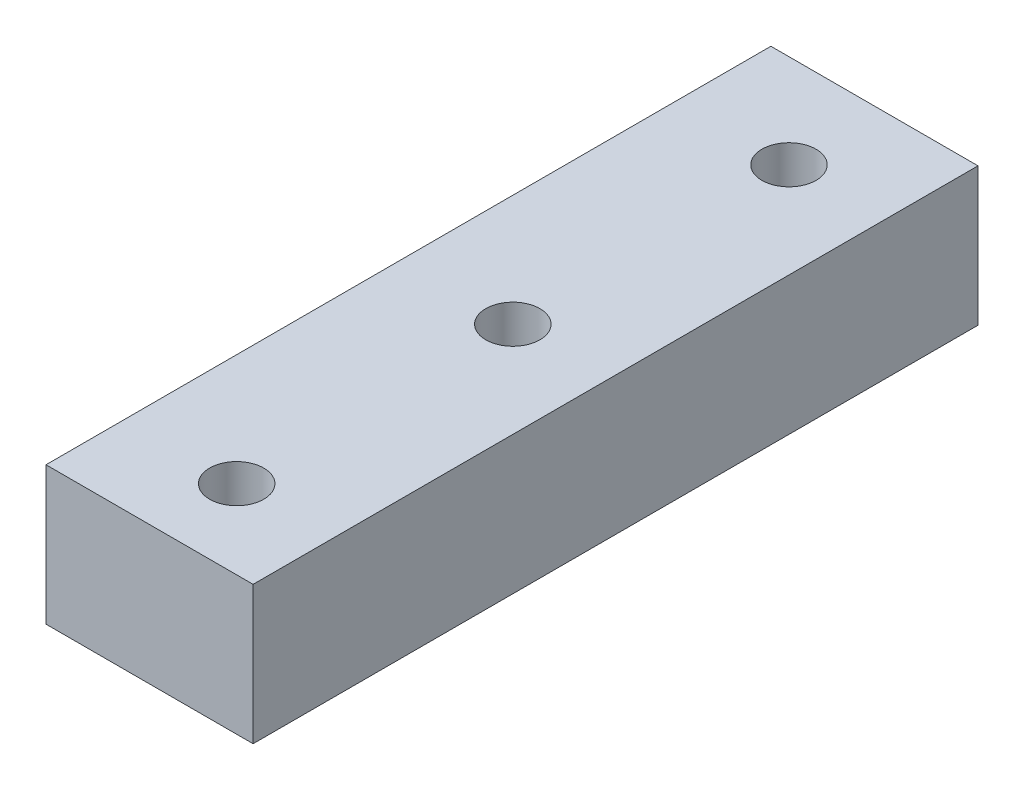
SolidWorks part; units mm, degrees
ref_plane "Front Plane" through (0, 0, 0) normal (0, 0, 1) x (1, 0, 0)
ref_plane "Top Plane" through (0, 0, 0) normal (0, 1, 0) x (1, 0, 0)
ref_plane "Right Plane" through (0, 0, 0) normal (1, 0, 0) x (0, 0, -1)
sketch "Sketch4" plane through (0, 0, 0) normal (0, 1, 0) x (1, 0, 0)
  line L8 (-61.3338, 18.9329) -> (-61.3338, -6.4671) construction
  line L9 (-61.3338, 6.2329) -> (-71.6088, 6.2329) construction
  line L10 (-71.6088, -0.9671) -> (-71.6088, 13.4329) construction
  line L11 (-71.6088, 6.2329) -> (-71.6088, 28.4579)
  line L12 (-71.6088, 28.4579) -> (-52.5588, 28.4579)
  line L13 (-52.5588, 28.4579) -> (-52.5588, -12.8171)
  line L15 (-71.6088, -12.8171) -> (-71.6088, 6.2329)
  line L16 (-52.5588, -12.8171) -> (-52.5588, -38.2171)
  line L17 (-71.6088, -12.8171) -> (-71.6088, -38.2171)
  line L18 (-71.6088, -38.2171) -> (-52.5588, -38.2171)
  point P10 (0, 0)
  dimension "D1" = 66.675
extrude "Boss-Extrude1" add sketch "Sketch4" along normal blind 12.7
sketch "Sketch5" plane through (0, 12.7, 0) normal (0, 1, 0) x (1, 0, 0)
  line L0 (-61.3338, -5.5524) -> (-61.3338, -30.9524) construction
  line L3 (-61.3338, 19.8476) -> (-61.3338, -5.5524) construction
  point P0 (0, 0)
hole_wizard "#10 Clearance Hole1" positions "Sketch6" profile "Sketch7" hole size "#10" standard "ANSI Inch" end condition through all
sketch "Sketch6" plane through (0, 12.7, 0) normal (0, 1, 0) x (1, 0, 0)
  point P0 (-61.3338, 19.8476)
  point P3 (-61.3338, -5.5524)
  point P6 (-61.3338, -30.9524)
sketch "Sketch7" plane through (-61.3338, 12.7, -19.8476) normal (1, 0, 0) x (0, 0, 1)
  line L0 (0, 0) -> (0, 12.7)
  line L1 (0, 12.7) -> (2.4892, 12.7)
  line L2 (2.4892, 12.7) -> (2.4892, 0)
  line L5 (2.4892, 0) -> (0, 0)
  line L11 (0, -6.35) -> (0, 107.95) construction
  dimension "Thru Hole Dia." = 4.9784
  dimension "Thru Hole Depth" = 12.7
